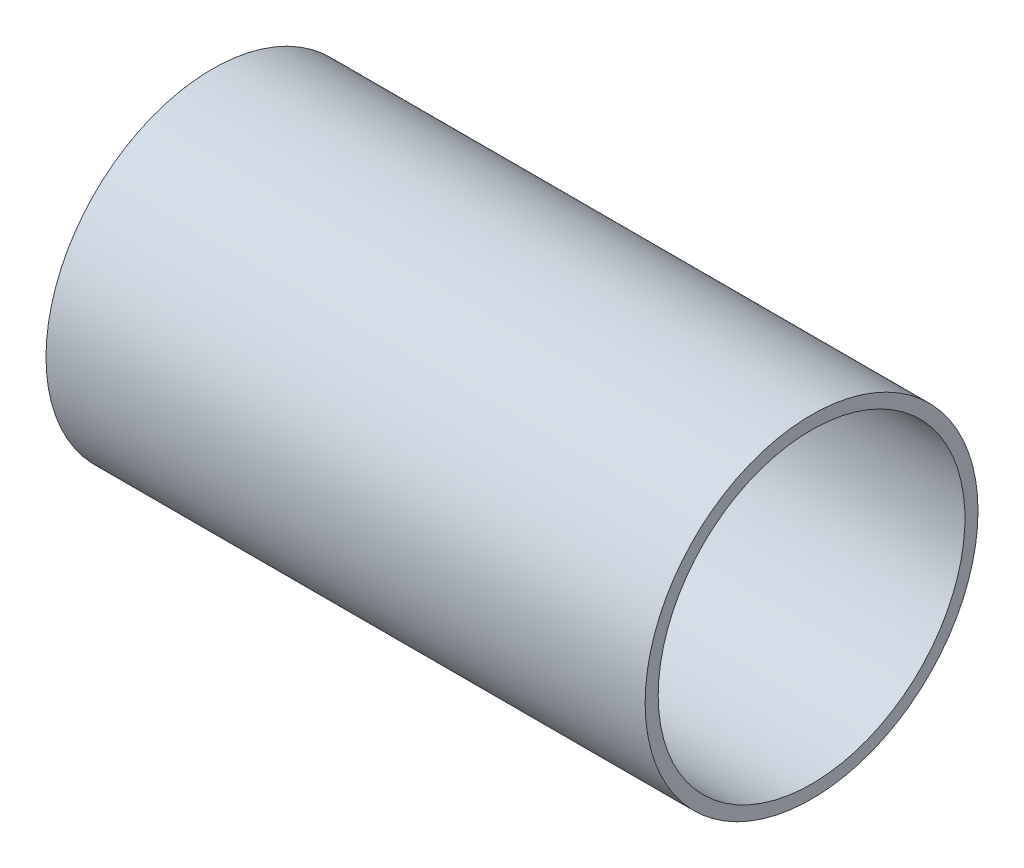
SolidWorks part; units mm, degrees
material "6061-T6 (SS)"
ref_plane "Front Plane" through (0, 0, 0) normal (0, 0, 1) x (1, 0, 0)
ref_plane "Top Plane" through (0, 0, 0) normal (0, 1, 0) x (1, 0, 0)
ref_plane "Right Plane" through (0, 0, 0) normal (1, 0, 0) x (0, 0, -1)
sketch "Sketch1" plane through (0, 0, 0) normal (0, 1, 0) x (1, 0, 0)
  line L0 (-72.894, 0) -> (78.2697, 0) construction
  line L1 (-28.575, 15.875) -> (-28.575, 14.6304)
  line L2 (-28.575, 15.875) -> (28.575, 15.875)
  line L3 (-28.575, 14.6304) -> (28.575, 14.6304)
  line L4 (28.575, 15.875) -> (28.575, 14.6304)
  line L5 (0, 0) -> (0, 14.6304) construction
  dimension "D1" = 31.75
  dimension "D2" = 1.2446
  dimension "D3" = 57.15
revolve "Revolve1" add sketch "Sketch1" angle 360 about L0
